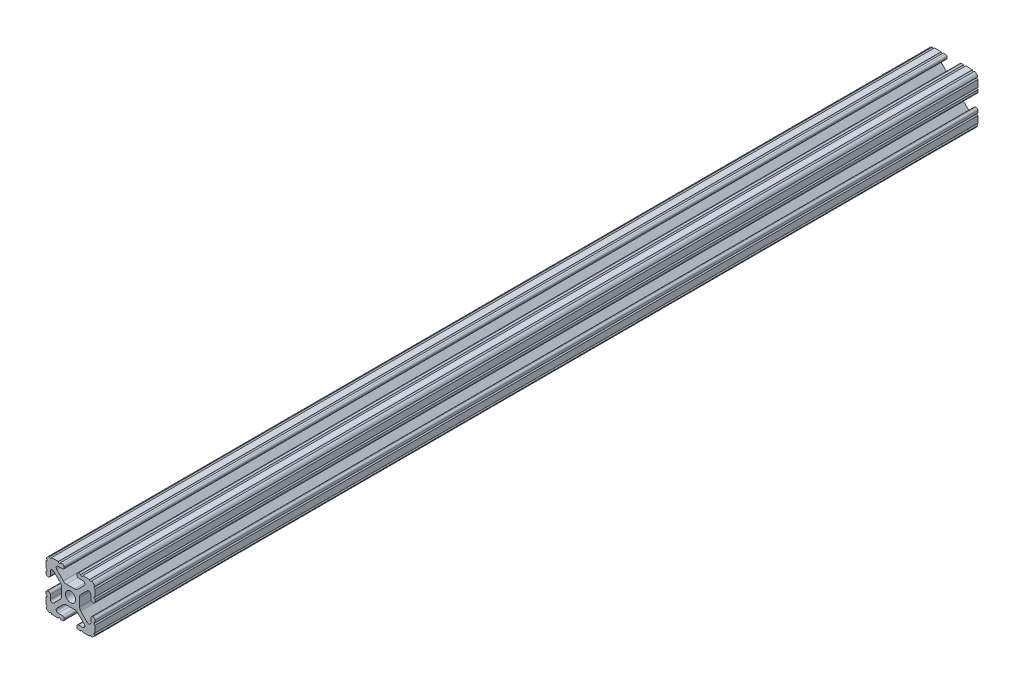
SolidWorks part; units mm, degrees
ref_plane "Front Plane" through (0, 0, 0) normal (0, 0, 1) x (1, 0, 0)
ref_plane "Top Plane" through (0, 0, 0) normal (0, 1, 0) x (1, 0, 0)
ref_plane "Right Plane" through (0, 0, 0) normal (1, 0, 0) x (0, 0, -1)
sketch "Sketch2" plane through (0, 0, 0) normal (0, 0, 1) x (1, 0, 0)
  line L0 (0, 12.7) -> (0, -12.7) construction
  line L1 (-12.7, 0) -> (12.7, 0) construction
  line L2 (3.2512, -12.7) -> (12.7, -12.7)
  line L3 (12.7, -12.7) -> (12.7, -3.2512)
  line L4 (3.2512, -12.7) -> (3.2512, -10.4902)
  line L5 (3.2512, -10.4902) -> (8.9276, -10.4902)
  line L6 (8.9276, -10.4902) -> (3.0856, -4.6482)
  line L7 (0, 0) -> (12.7, -12.7) construction
  line L8 (12.7, -3.2512) -> (10.4902, -3.2512)
  line L9 (10.4902, -3.2512) -> (10.4902, -8.9276)
  line L10 (10.4902, -8.9276) -> (4.6482, -3.0856)
  circle A0 centre (0, 0) radius 2.6035
  arc A1 (6.3485, -10.4902) -> (7.1039, -8.6665) centre (6.3485, -9.4219) ccw construction
  point P8 (0, -4.6482)
  dimension "Center Hole Diameter" = 5.207
  dimension "Rail Height" = 25.4
  dimension "Rail Width" = 25.4
  dimension "T-Slot Width" = 6.5024
  dimension "Slot Inner Width" = 14.8336
  dimension "Thickness" = 2.2098
  dimension "Slot Depth" = 5.842
  dimension "D1" = 2.2098
sketch "Sketch3" plane through (0, 0, 0) normal (1, 0, 0) x (0, 0, -1)
  line L0 (-228.6, -12.7) -> (228.6, -12.7) construction
  line L1 (-203.2, 0) -> (203.2, 0) construction
  dimension "Length" = 457.2
  dimension "D1" = 25.4
sketch "Sketch4" plane through (0, 0, 0) normal (0, 0, 1) x (1, 0, 0)
  line L0 (4.1904, -12.7) -> (10.1173, -12.7)
  line L1 (3.2512, -12.7) -> (12.7, -12.7) construction
  line L2 (3.2512, -12.7) -> (3.2512, -10.4902) construction
  line L3 (3.2512, -10.4902) -> (8.9276, -10.4902) construction
  line L4 (3.2512, -11.4294) -> (3.2512, -11.7608)
  line L5 (4.1904, -10.4902) -> (6.3485, -10.4902)
  line L6 (0, -4.6482) -> (2.164, -4.6482)
  line L7 (8.9276, -10.4902) -> (3.0856, -4.6482) construction
  line L8 (3.7373, -5.2999) -> (7.1039, -8.6665)
  line L9 (12.7, -12.7) -> (12.7, -3.2512) construction
  line L10 (10.4902, -8.9276) -> (4.6482, -3.0856) construction
  line L11 (10.4902, -3.2512) -> (10.4902, -8.9276) construction
  line L12 (10.4902, -6.3485) -> (10.4902, -4.1904)
  line L13 (12.7, -3.2512) -> (10.4902, -3.2512) construction
  line L14 (11.4294, -3.2512) -> (11.7608, -3.2512)
  line L15 (12.7, -4.1904) -> (12.7, -10.1173)
  line L16 (8.6665, -7.1039) -> (5.2999, -3.7373)
  line L17 (4.6482, 0) -> (4.6482, -2.164)
  line L18 (-12.7, 0) -> (12.7, 0) construction
  line L19 (0, -4.6482) -> (0, -2.6035)
  line L20 (0, 12.7) -> (0, -12.7) construction
  line L21 (4.6482, 0) -> (2.6035, 0)
  arc A0 (3.2512, -11.7608) -> (4.1904, -12.7) centre (4.1904, -11.7608) ccw
  arc A2 (3.2512, -11.4294) -> (4.1904, -10.4902) centre (4.1904, -11.4294) cw
  arc A3 (6.3485, -10.4902) -> (7.1039, -8.6665) centre (6.3485, -9.4219) ccw
  arc A4 (2.164, -4.6482) -> (3.7373, -5.2999) centre (2.164, -6.8732) cw
  arc A5 (10.1173, -12.7) -> (12.7, -10.1173) centre (10.1173, -10.1173) ccw
  arc A6 (8.6665, -7.1039) -> (10.4902, -6.3485) centre (9.4219, -6.3485) ccw
  arc A7 (10.4902, -4.1904) -> (11.4294, -3.2512) centre (11.4294, -4.1904) cw
  arc A8 (11.7608, -3.2512) -> (12.7, -4.1904) centre (11.7608, -4.1904) cw
  arc A9 (5.2999, -3.7373) -> (4.6482, -2.164) centre (6.8732, -2.164) cw
  circle A10 centre (0, 0) radius 2.6035 construction
  arc A11 (0, -2.6035) -> (2.6035, 0) centre (0, 0) ccw
  dimension "D1" = 2.5827
  dimension "D2" = 2.225
  dimension "D3" = 0.9392
extrude "Boss-Extrude1" add sketch "Sketch4" along normal mid plane 457.2
sketch "Sketch5" plane through (0, 0, 0) normal (0, 0, 1) x (1, 0, 0)
  line L0 (3.2512, -12.7) -> (12.7, -12.7) construction
  line L1 (4.1904, -10.4902) -> (6.3485, -10.4902) construction
  line L3 (0, 0) -> (12.7, -12.7) construction
  line L4 (6.3485, -10.4902) -> (6.3485, -12.7) construction
  line L5 (8.9276, -10.4902) -> (3.0856, -4.6482) construction
  circle A0 centre (10.3562, -12.7) radius 0.5524
  circle A1 centre (5.796, -12.7) radius 0.5524
  circle A2 centre (12.7, -10.3562) radius 0.5524
  circle A3 centre (12.7, -5.796) radius 0.5524
  point P10 (5.2694, -10.4902)
  point P12 (9.4219, -6.3485)
  dimension "D1" = 1.1049
extrude "Cut-Extrude1" cut sketch "Sketch5" against normal through all both and the other way through all
mirror "Mirror1" about plane through (0, 0, 0) normal (1, 0, 0) of bodies 137 134
mirror "Mirror2" about plane through (0, 0, 0) normal (0, 1, 0) of bodies 135
equation "\"D1@Boss-Extrude1\"=\"Length@Sketch3\""
equation "\"D1@Sketch2\"=\"Thickness@Sketch2\""
equation "\"D2@Sketch4\"=\"Slot Inner Width@Sketch2\"*0.15"
equation "\"D1@Sketch4\"=\"D3@Sketch4\"*2.75"
equation "\"D3@Sketch4\"=\"Thickness@Sketch2\"*0.425"
equation "\"D1@Sketch5\"=\"Thickness@Sketch2\"*0.5"
